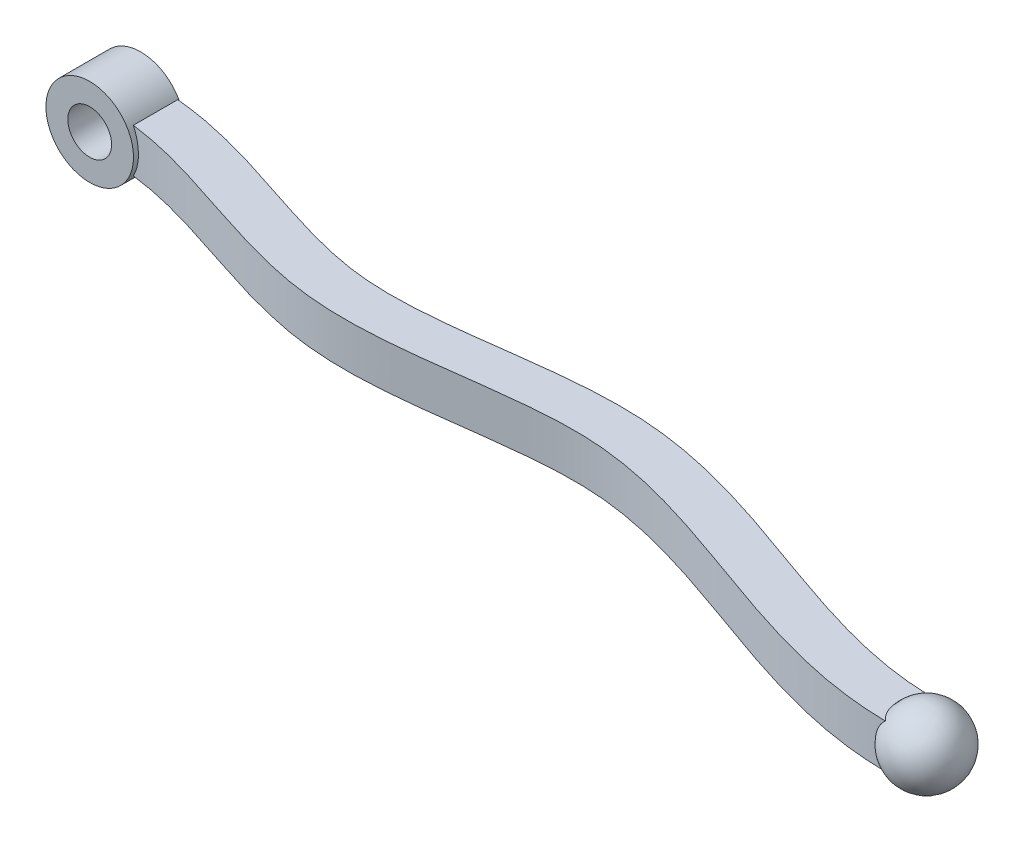
SolidWorks part; units mm, degrees
material "AISI 1020 Steel, Cold Rolled"
ref_plane "Front Plane" through (0, 0, 0) normal (0, 0, 1) x (1, 0, 0)
ref_plane "Top Plane" through (0, 0, 0) normal (0, 1, 0) x (1, 0, 0)
ref_plane "Right Plane" through (0, 0, 0) normal (1, 0, 0) x (0, 0, -1)
sketch "Sketch1" plane through (0, 0, 0) normal (0, 1, 0) x (1, 0, 0)
  line L0 (0, -5) -> (0, -20)
  line L1 (0, 0) -> (650, 0) construction
  line L2 (0, 0) -> (0, -116.75) construction
  line L3 (0, -116.75) -> (650, -116.75) construction
  line L4 (650, 0) -> (650, -116.75) construction
  line L5 (0, -35) -> (0, -20)
  line L6 (650, -131.75) -> (650, -101.6456)
  spline S2 degree 3 poles (0, -35) (6.1752, -34.732) (18.5153, -35.013) (37.1707, -37.5159) (56.0849, -41.7259) (81.7128, -49.0537) (108.0205, -58.039) (135.2566, -66.6168) (156.2604, -72.2744) (174.3016, -75.8428) (189.1658, -77.6735) (203.9933, -78.726) (222.3714, -78.7968) (251.388, -76.9754) (286.8505, -72.3876) (321.0104, -67.8884) (347.2959, -66.038) (363.239, -65.9213) (375.6513, -66.6337) (388.1098, -67.9093) (403.7497, -70.4723) (422.6823, -74.8769) (448.1747, -82.1945) (480.5555, -93.4084) (520.4277, -107.9436) (554.7671, -118.9729) (583.1157, -125.8726) (604.86, -129.7434) (623.4235, -131.587) (638.5124, -132.052) (646.1844, -131.9156) (650, -131.75) knots 0 0 0 0 0.03125 0.0625 0.09375 0.125 0.1875 0.21875 0.25 0.28125 0.296875 0.3125 0.34375 0.375 0.4375 0.5 0.53125 0.5625 0.578125 0.59375 0.625 0.65625 0.6875 0.75 0.8125 0.875 0.90625 0.9375 0.96875 0.984375 1 1 1 1
  spline S4 degree 3 poles (0, -5) (1.9612, -4.9146) (5.8992, -4.8082) (13.6782, -4.8466) (23.2888, -5.3356) (34.6121, -6.543) (49.4404, -8.8658) (67.481, -12.8953) (88.425, -18.8945) (108.7644, -25.4669) (128.5843, -32.0579) (147.9493, -38.1439) (166.8899, -43.2309) (182.3743, -46.2693) (194.5455, -47.7651) (206.9087, -48.645) (222.7716, -48.7172) (248.9492, -47.0877) (282.9936, -42.7135) (318.3597, -38.0169) (347.3056, -35.9576) (365.6377, -35.8029) (380.4458, -36.6493) (395.0719, -38.1479) (413.0617, -41.1023) (434.1959, -46.0254) (461.8406, -53.9664) (495.5333, -65.6518) (534.9867, -80.0209) (573.7465, -92.4233) (611.962, -100.7027) (637.3049, -102.1986) (650, -101.6456) knots 0 0 0 0 0.007812 0.015625 0.03125 0.046875 0.0625 0.09375 0.125 0.15625 0.1875 0.21875 0.25 0.28125 0.296875 0.3125 0.34375 0.375 0.4375 0.5 0.53125 0.5625 0.578125 0.59375 0.625 0.65625 0.6875 0.75 0.8125 0.875 0.9375 1 1 1 1
  dimension "D1" = 116.75
  dimension "D2" = 650
  dimension "D3" = 20
extrude "Boss-Extrude1" add sketch "Sketch1" along normal mid plane 30
ref_plane "Plane1" through (0, 0, 5) normal (0, 0, 1) x (1, 0, 0)
sketch "Sketch5" plane through (0, 0, 5) normal (0, 0, 1) x (1, 0, 0)
  circle A0 centre (0, 0) radius 30
  dimension "D1" = 60
extrude "Boss-Extrude4" add sketch "Sketch5" along normal blind 35
sketch "Sketch6" plane through (0, 0, 40) normal (0, 0, 1) x (1, 0, 0)
  circle A0 centre (0, 0) radius 15
  dimension "D1" = 30
extrude "Cut-Extrude2" cut sketch "Sketch6" against normal through all
sketch "Sketch8" plane through (0, 0, 0) normal (0, 1, 0) x (1, 0, 0)
  line L0 (650, -131.75) -> (650, -101.6456) construction
  line L1 (650, -91.6978) -> (650, -141.6978)
  arc A0 (650, -91.6978) -> (650, -141.6978) centre (650, -116.6978) cw
  dimension "D1" = 25
revolve "Revolve2" add sketch "Sketch8" angle 360 about L1
